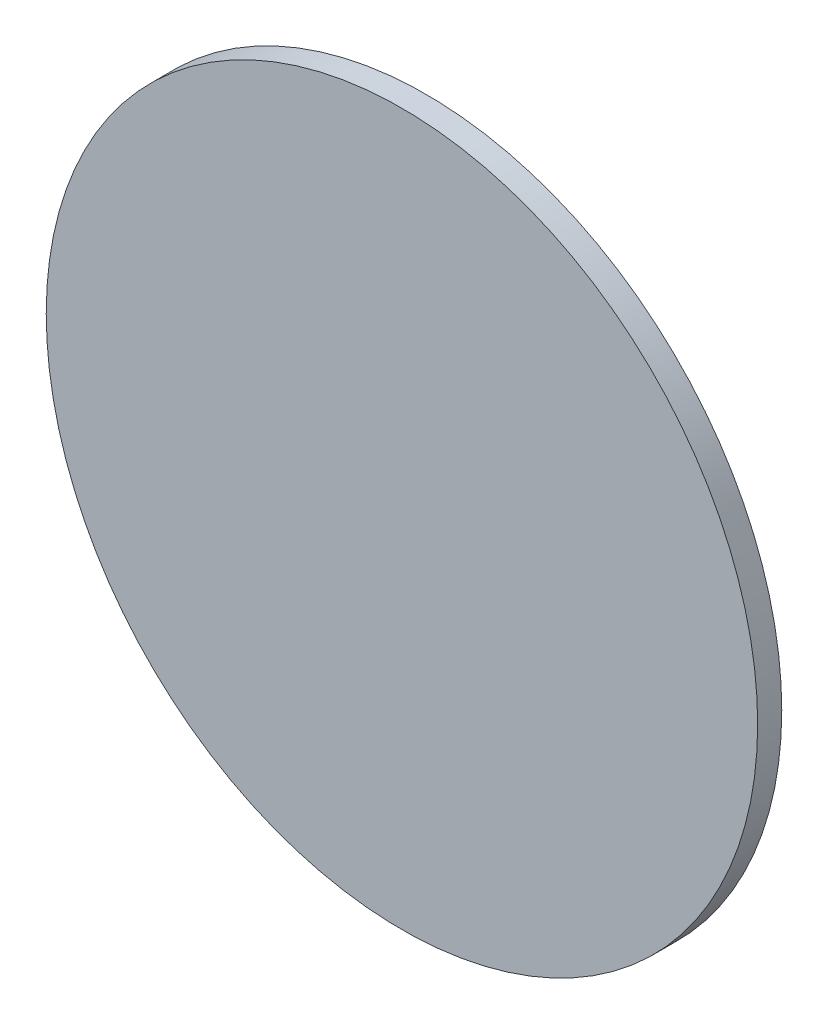
SolidWorks part; units mm, degrees
ref_plane "Front Plane" through (0, 0, 0) normal (0, 0, 1) x (1, 0, 0)
ref_plane "Top Plane" through (0, 0, 0) normal (0, 1, 0) x (1, 0, 0)
ref_plane "Right Plane" through (0, 0, 0) normal (1, 0, 0) x (0, 0, -1)
sketch "CurveSketch" plane through (0, 0, 0) normal (0, 0, 1) x (1, 0, 0)
  circle A0 centre (-3.719, 5.173) radius 173.217
  dimension "D1" = 173.217
extrude "CurveBoss" add sketch "CurveSketch" along normal blind 11.731
